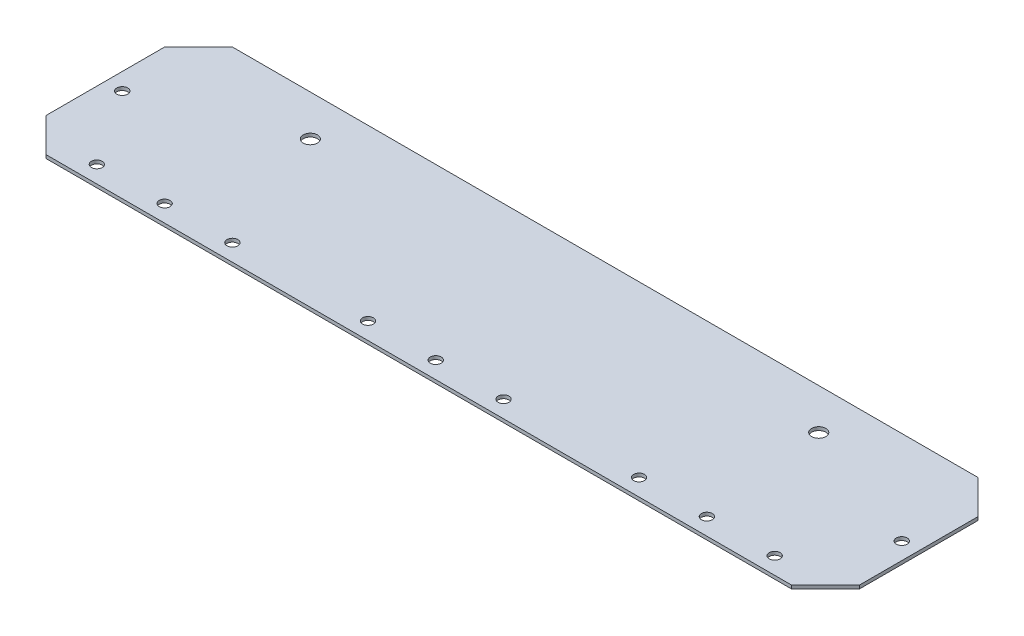
SolidWorks part; units mm, degrees
ref_plane "前视基准面" through (0, 0, 0) normal (0, 0, 1) x (1, 0, 0)
ref_plane "上视基准面" through (0, 0, 0) normal (0, 1, 0) x (1, 0, 0)
ref_plane "右视基准面" through (0, 0, 0) normal (1, 0, 0) x (0, 0, -1)
other "Configuration Table"
sketch "草图1" plane through (0, 0, 0) normal (0, 1, 0) x (1, 0, 0)
  line L1 (0, 0) -> (240, 0)
  line L2 (0, 0) -> (0, 55)
  line L3 (0, 55) -> (240, 55)
  line L4 (240, 0) -> (240, 55)
  dimension "D1" = 240
  dimension "D2" = 55
extrude "凸台-拉伸1" add sketch "草图1" along normal blind 1
chamfer "倒角1" distance 10 angle 45 4 edges at (0, 0.5, -55) (240, 0.5, 0) (0, 0.5, 0) (240, 0.5, -55)
sketch "草图2" plane through (0, 0, 0) normal (0, -1, 0) x (1, 0, 0)
  line L0 (195, -43) -> (45, -43) construction
  line L1 (120, -43) -> (120, -55) construction
  line L2 (230, -55) -> (10, -55) construction
  line L3 (235, -27.5) -> (240, -27.5) construction
  line L4 (240, -10) -> (240, -45) construction
  line L5 (5, -27.5) -> (0, -27.5) construction
  line L6 (0, -45) -> (0, -10) construction
  line L7 (20, -5) -> (60, -5) construction
  line L8 (60, -5) -> (100, -5) construction
  line L9 (100, -5) -> (140, -5) construction
  line L10 (80, -5) -> (80, 0) construction
  line L12 (10, 0) -> (230, 0) construction
  line L13 (120, -5) -> (120, 0) construction
  line L14 (160, -5) -> (160, 0) construction
  line L15 (180, -5) -> (140, -5) construction
  line L16 (220, -5) -> (180, -5) construction
  circle A0 centre (195, -43) radius 2.1
  circle A1 centre (45, -43) radius 2.1
  circle A2 centre (235, -27.5) radius 1.6
  circle A3 centre (5, -27.5) radius 1.6
  circle A4 centre (20, -5) radius 1.6
  circle A5 centre (60, -5) radius 1.6
  circle A6 centre (100, -5) radius 1.6
  circle A8 centre (140, -5) radius 1.6
  circle A9 centre (180, -5) radius 1.6
  circle A10 centre (220, -5) radius 1.6
  circle A11 centre (40, -5) radius 1.6
  circle A12 centre (120, -5) radius 1.6
  circle A13 centre (200, -5) radius 1.6
  dimension "D1" = 4.2
  dimension "D4" = 3.2
  dimension "D6" = 3.2
  dimension "D8" = 3.2
  dimension "D2" = 150
  dimension "D3" = 12
  dimension "D5" = 5
  dimension "D7" = 5
  dimension "D9" = 5
  dimension "D10" = 40
extrude "切除-拉伸1" cut sketch "草图2" against normal blind 10
